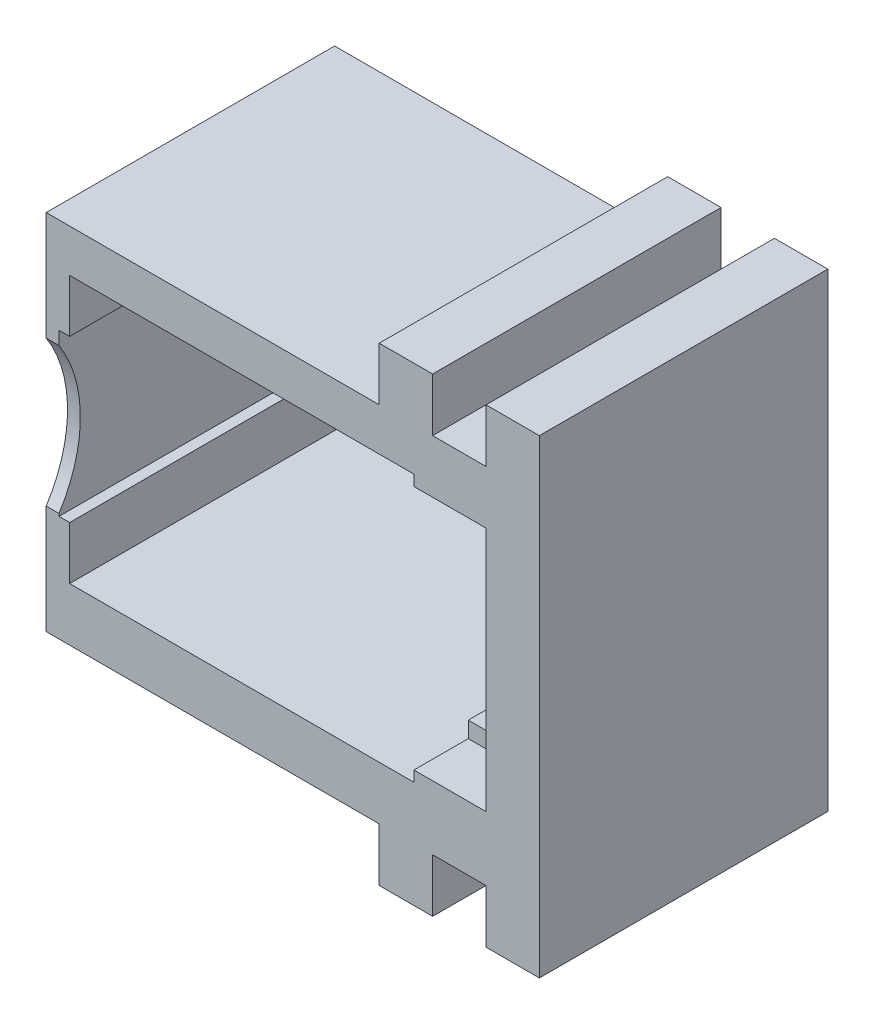
SolidWorks part; units mm, degrees
ref_plane "Front Plane" through (0, 0, 0) normal (0, 0, 1) x (1, 0, 0)
ref_plane "Top Plane" through (0, 0, 0) normal (0, 1, 0) x (1, 0, 0)
ref_plane "Right Plane" through (0, 0, 0) normal (1, 0, 0) x (0, 0, -1)
sketch "Sketch1" plane through (0, 0, 0) normal (0, 0, 1) x (1, 0, 0)
  line L1 (-28.3549, -0.0968) -> (9.8451, -0.0968)
  line L2 (-28.3549, -0.0968) -> (-28.3549, -30.0968)
  line L3 (-28.3549, -30.0968) -> (9.8451, -30.0968)
  line L4 (9.8451, -0.0968) -> (9.8451, -30.0968)
extrude "Boss-Extrude1" add sketch "Sketch1" along normal blind 2
sketch "Sketch2" plane through (0, 0, 2) normal (0, 0, 1) x (1, 0, 0)
  line L0 (9.8451, -30.0968) -> (9.8451, -0.0968) construction
  line L1 (-28.3549, -0.0968) -> (9.8451, -0.0968)
  line L2 (-28.3549, -0.0968) -> (-28.3549, -2.0968)
  line L3 (-28.3549, -2.0968) -> (9.8451, -2.0968)
  line L4 (9.8451, -0.0968) -> (9.8451, -2.0968)
  line L5 (-28.3549, -30.0968) -> (9.8451, -30.0968) construction
  line L10 (9.8451, -30.0968) -> (6.0951, -30.0968)
  line L11 (9.8451, -30.0968) -> (9.8451, -24.5968)
  line L12 (9.8451, -24.5968) -> (6.0951, -24.5968)
  line L13 (6.0951, -30.0968) -> (6.0951, -24.5968)
  line L14 (9.8451, -24.5968) -> (7.8451, -24.5968)
  line L15 (9.8451, -24.5968) -> (9.8451, -4.5968)
  line L16 (9.8451, -4.5968) -> (7.8451, -4.5968)
  line L17 (7.8451, -24.5968) -> (7.8451, -4.5968)
  line L18 (9.8451, -4.5968) -> (6.0951, -4.5968)
  line L19 (9.8451, -4.5968) -> (9.8451, -2.0968)
  line L20 (9.8451, -2.0968) -> (6.0951, -2.0968)
  line L21 (6.0951, -4.5968) -> (6.0951, -2.0968)
  line L22 (-28.3549, -2.0968) -> (-26.1549, -2.0968)
  line L23 (-28.3549, -2.0968) -> (-28.3549, -30.0968)
  line L24 (-28.3549, -30.0968) -> (-26.1549, -30.0968)
  line L25 (-26.1549, -2.0968) -> (-26.1549, -30.0968)
  line L28 (-26.1549, -22.1468) -> (-27.1549, -22.1468)
  line L29 (-26.1549, -22.1468) -> (-26.1549, -7.0468)
  line L30 (-26.1549, -7.0468) -> (-27.1549, -7.0468)
  line L31 (-27.1549, -22.1468) -> (-27.1549, -7.0468)
  line M9 (-28.3549, -0.0968) -> (-28.3549, -30.0968)
  line M10 (-28.3549, -30.0968) -> (9.8451, -30.0968)
  line M11 (9.8451, -30.0968) -> (9.8451, -0.0968)
  line M12 (9.8451, -0.0968) -> (-28.3549, -0.0968)
extrude "Boss-Extrude2" add sketch "Sketch2" along normal blind 27.02 contours L28 L31 L30 L25 L3 M9 M10 | L3 M9 M11 M12 | L21 L18 L16 L3 M11 | L17 L12 L16 M11 | L13 L12 M10 M11
sketch "Sketch3" plane through (9.8451, 0, 0) normal (1, 0, 0) x (0, 0, -1)
  line L0 (-29.02, -30.0968) -> (-29.02, -0.0968) construction
  line L1 (-29.02, -3.0968) -> (-21.93, -3.0968)
  line L2 (-29.02, -3.0968) -> (-29.02, -26.0968)
  line L3 (-29.02, -26.0968) -> (-21.93, -26.0968)
  line L4 (-21.93, -3.0968) -> (-21.93, -26.0968)
  line L5 (0, -30.0968) -> (0, -0.0968) construction
  line L6 (-29.02, -0.0968) -> (0, -0.0968) construction
  dimension "D1" = 21.93
  dimension "D2" = 3
  dimension "D3" = 23
extrude "Cut-Extrude1" cut sketch "Sketch3" against normal up to next
sketch "Sketch4" plane through (-28.3549, 0, 0) normal (-1, 0, 0) x (0, 0, 1)
  line L0 (29.02, -2.0968) -> (2, -2.0968) construction
  line L1 (0, -30.0968) -> (37.62, -30.0968)
  line L2 (0, -30.0968) -> (0, -15.0968)
  line L3 (0, -15.0968) -> (37.62, -15.0968)
  line L4 (37.62, -30.0968) -> (37.62, -15.0968)
  line L5 (29.02, -7.0468) -> (2, -7.0468) construction
  circle A0 centre (37.62, -15.0968) radius 12.6
  line M7 (29.02, -30.0968) -> (29.02, -0.0968)
  dimension "D1" = 4.95
extrude "Cut-Extrude3" cut sketch "Sketch4" against normal up to next contours L3 A0 M7 | A0 L3 M7
sketch "Sketch6" plane through (-28.3549, 0, 0) normal (-1, 0, 0) x (0, 0, 1)
  line L0 (29.02, -30.0968) -> (0, -30.0968) construction
  line L1 (29.02, -0.0968) -> (2.02, -0.0968)
  line L2 (29.02, -0.0968) -> (29.02, -30.0968)
  line L3 (29.02, -30.0968) -> (2.02, -30.0968)
  line L4 (2.02, -0.0968) -> (2.02, -30.0968)
  line L6 (2.02, -0.0968) -> (27.02, -0.0968)
  line L7 (2.02, -0.0968) -> (2.02, -30.0968)
  line L8 (2.02, -30.0968) -> (27.02, -30.0968)
  line L9 (27.02, -0.0968) -> (27.02, -30.0968)
  line M9 (29.02, -30.0968) -> (29.02, -24.3055)
  arc M10 (29.02, -24.3055) -> (29.02, -5.8881) centre (37.62, -15.0968) cw
  line M11 (29.02, -5.8881) -> (29.02, -0.0968)
  line M12 (29.02, -0.0968) -> (0, -0.0968)
  dimension "D1" = 2
extrude "Cut-Extrude4" cut sketch "Sketch6" against normal through all both and the other way through all contours L9 L3 M10 M9 | L9 M12 M10 M11
sketch "Sketch7" plane through (0, 0, 2) normal (0, 0, 1) x (1, 0, 0)
  line L0 (6.0951, -26.0968) -> (6.0951, -30.0968) construction
  line L1 (-26.1549, -30.0968) -> (6.0951, -30.0968)
  line L2 (-26.1549, -30.0968) -> (-26.1549, -27.0968)
  line L3 (-26.1549, -27.0968) -> (6.0951, -27.0968)
  line L4 (6.0951, -30.0968) -> (6.0951, -27.0968)
extrude "Boss-Extrude3" add sketch "Sketch7" along normal up to surface (25.02 mm away) up to face at (7.9701, -28.0968, 27.02)
sketch "Sketch8" plane through (-28.3549, 0, 0) normal (-1, 0, 0) x (0, 0, 1)
  line L0 (27.02, -0.0968) -> (0, -0.0968) construction
  line L1 (0, -30.0968) -> (20, -30.0968)
  line L2 (0, -30.0968) -> (0, -0.0968)
  line L3 (0, -0.0968) -> (20, -0.0968)
  line L4 (20, -30.0968) -> (20, -0.0968)
extrude "Boss-Extrude4" add sketch "Sketch8" along normal blind 5
sketch "Sketch9" plane through (0, -30.0968, 0) normal (0, -1, 0) x (1, 0, 0)
  line L0 (-33.3549, 20) -> (-28.3549, 20)
  line L1 (-28.3549, 20) -> (-28.3549, 27.02)
  line L2 (-28.3549, 27.02) -> (9.8451, 27.02)
  line L3 (9.8451, 27.02) -> (9.8451, 0)
  line L4 (9.8451, 0) -> (-33.3549, 0)
  line L5 (-33.3549, 0) -> (-33.3549, 20)
extrude "Boss-Extrude5" add sketch "Sketch9" along normal blind 2
sketch "Sketch10" plane through (9.8451, 0, 0) normal (1, 0, 0) x (0, 0, -1)
  line L0 (-27.02, 0) -> (0, -0.0968)
  line L2 (-27.02, -0.0968) -> (-27.02, 0)
  line L4 (0, -0.0968) -> (0, 0)
  line L6 (0, -0.0968) -> (0, -32.0968)
  line L7 (0, -32.0968) -> (-27.02, -32.0968)
  line L8 (-27.02, -32.0968) -> (-27.02, -26.0968)
  line L9 (-27.02, -26.0968) -> (-21.93, -26.0968)
  line L10 (-21.93, -26.0968) -> (-21.93, -3.0968)
  line L11 (-21.93, -3.0968) -> (-27.02, -3.0968)
  line L12 (-21.93, -3.0968) -> (-27.02, -3.0968) construction
  line L13 (-27.02, -3.0968) -> (-27.02, 0)
  line M1 (-21.93, -26.0968) -> (-27.02, -26.0968)
  line M2 (-27.02, -26.0968) -> (-27.02, -32.0968)
  line M3 (-27.02, -32.0968) -> (0, -32.0968)
  line M4 (0, -32.0968) -> (0, -0.0968)
  line M5 (0, -0.0968) -> (-27.02, -0.0968)
  line M6 (-27.02, -0.0968) -> (-27.02, -3.0968)
  line M7 (-27.02, -3.0968) -> (-21.93, -3.0968)
  line M8 (-21.93, -3.0968) -> (-21.93, -26.0968)
extrude "Boss-Extrude6" add sketch "Sketch10" along normal blind 3 contours M8 M1 M2 M3 M4 M5 M6 M7
sketch "Sketch11" plane through (0, -0.0968, 0) normal (0, 1, 0) x (1, 0, 0)
  line L0 (-33.3549, 0) -> (-33.3549, -20)
  line L1 (-33.3549, -20) -> (-28.3549, -20)
  line L2 (-28.3549, -20) -> (-28.3549, -27.02)
  line L3 (-28.3549, -27.02) -> (12.8451, -27.02)
  line L4 (12.8451, -27.02) -> (12.8451, 0)
  line L5 (12.8451, 0) -> (-33.3549, 0)
extrude "Boss-Extrude7" add sketch "Sketch11" along normal blind 2
sketch "Sketch12" plane through (0, 1.9032, 0) normal (0, 1, 0) x (1, 0, 0)
  line L0 (-28.3549, -27.02) -> (12.8451, -27.02) construction
  line L1 (12.8451, 0) -> (7.8451, 0)
  line L2 (12.8451, 0) -> (12.8451, -27.02)
  line L3 (12.8451, -27.02) -> (7.8451, -27.02)
  line L4 (7.8451, 0) -> (7.8451, -27.02)
  line L6 (7.8451, 0) -> (2.8451, 0)
  line L7 (7.8451, 0) -> (7.8451, -27.02)
  line L8 (7.8451, -27.02) -> (2.8451, -27.02)
  line L9 (2.8451, 0) -> (2.8451, -27.02)
  line M9 (12.8451, 0) -> (-33.3549, 0)
  line M13 (-28.3549, -27.02) -> (12.8451, -27.02)
  dimension "D1" = 10
  dimension "D2" = 5
extrude "Boss-Extrude8" add sketch "Sketch12" along normal blind 5 contours L9 L4 M9 M13
sketch "Sketch13" plane through (0, 6.9032, 0) normal (0, 1, 0) x (1, 0, 0)
  line L1 (12.8451, 0) -> (17.8451, 0)
  line L2 (12.8451, 0) -> (12.8451, -22)
  line L3 (12.8451, -22) -> (17.8451, -22)
  line L4 (17.8451, 0) -> (17.8451, -22)
extrude "Boss-Extrude10" add sketch "Sketch13" against normal blind 44
sketch "Sketch15" plane through (0, -32.0968, 0) normal (0, -1, 0) x (-1, 0, 0)
  line L0 (33.3549, 0) -> (-12.8451, 0) construction
  line L1 (-12.8451, -27.02) -> (-2.8451, -27.02)
  line L2 (-12.8451, -27.02) -> (-12.8451, 0)
  line L3 (-12.8451, 0) -> (-2.8451, 0)
  line L4 (-2.8451, -27.02) -> (-2.8451, 0)
  line L5 (-7.8451, -27.02) -> (-7.8451, 0)
  line M6 (33.3549, 0) -> (-12.8451, 0)
extrude "Boss-Extrude11" add sketch "Sketch15" along normal blind 5 contours L5 L1 L4 M6
sketch "Sketch16" plane through (0, 0, 22) normal (0, 0, 1) x (1, 0, 0)
  line L1 (12.8451, -37.0968) -> (17.8451, -37.0968)
  line L2 (12.8451, -37.0968) -> (12.8451, 6.9032)
  line L3 (12.8451, 6.9032) -> (17.8451, 6.9032)
  line L4 (17.8451, -37.0968) -> (17.8451, 6.9032)
extrude "Boss-Extrude12" add sketch "Sketch16" along normal up to surface (5.02 mm away) and the other way blind 2 up to face at (-7.4763, -28.7267, 27.02)
sketch "Sketch17" plane through (-33.3549, 0, 0) normal (-1, 0, 0) x (0, 0, 1)
  line L1 (0, 1.9032) -> (20, 1.9032)
  line L2 (0, 1.9032) -> (0, -32.0968)
  line L3 (0, -32.0968) -> (20, -32.0968)
  line L4 (20, 1.9032) -> (20, -32.0968)
extrude "Cut-Extrude5" cut sketch "Sketch17" against normal up to surface (5 mm away) up to face at (-28.3549, -15.6596, 24.68)
